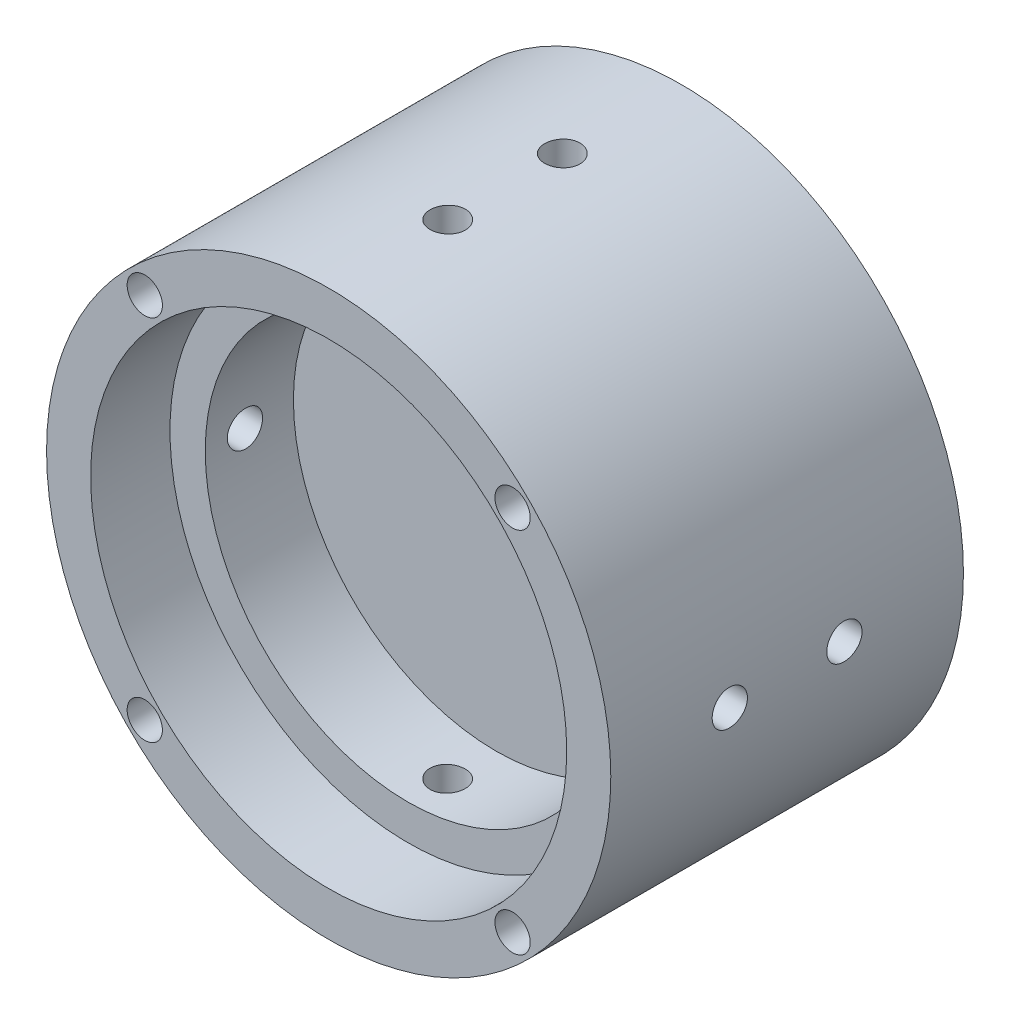
SolidWorks part; units mm, degrees
ref_plane "Front Plane" through (0, 0, 0) normal (0, 0, 1) x (1, 0, 0)
ref_plane "Top Plane" through (0, 0, 0) normal (0, 1, 0) x (1, 0, 0)
ref_plane "Right Plane" through (0, 0, 0) normal (1, 0, 0) x (0, 0, -1)
sketch "Sketch1" plane through (0, 0, 0) normal (0, 0, 1) x (1, 0, 0)
  circle A0 centre (0, 0) radius 80
extrude "Boss-Extrude1" add sketch "Sketch1" along normal blind 100
sketch "Sketch2" plane through (0, 0, 100) normal (0, 0, 1) x (1, 0, 0)
  circle A0 centre (0, 0) radius 67.5
extrude "Cut-Extrude1" cut sketch "Sketch2" against normal blind 22.5 contours A0
sketch "Sketch3" plane through (0, 0, 77.5) normal (0, 0, 1) x (1, 0, 0)
  circle A0 centre (0, 0) radius 57.5
extrude "Cut-Extrude2" cut sketch "Sketch3" against normal blind 25
sketch "Sketch6" plane through (0, 0, 0) normal (0, 1, 0) x (1, 0, 0)
  circle A0 centre (0, -66.25) radius 5
  point P6 (6.6984, -66.25)
  point P7 (0, 0)
extrude "Cut-Extrude3" cut sketch "Sketch6" against normal blind 184 and the other way blind 175
sketch "Sketch7" plane through (0, 0, 0) normal (1, 0, 0) x (0, 0, -1)
  line L0 (-100, 0) -> (-66.25, 0)
  line L1 (-100, 80) -> (-100, -80) construction
  circle A0 centre (-66.25, 0) radius 5
extrude "Cut-Extrude4" cut sketch "Sketch7" against normal blind 199 and the other way blind 233 contours A0
sketch "Sketch8" plane through (0, 0, 0) normal (0, 0, 1) x (1, 0, 0)
  circle A0 centre (0, 0) radius 67.5
extrude "Cut-Extrude5" cut sketch "Sketch8" along normal blind 22.5
sketch "Sketch9" plane through (0, 0, 0) normal (0, 0, 1) x (1, 0, 0)
  circle A0 centre (0, 0) radius 57.5
extrude "Cut-Extrude6" cut sketch "Sketch9" along normal blind 45
sketch "Sketch10" plane through (0, 0, 0) normal (0, 0, 1) x (1, 0, 0)
  line L0 (0, 0) -> (-56.5685, 56.5685)
  line L1 (56.5685, 56.5685) -> (-56.5685, -56.5685)
  line L2 (-56.5685, 56.5685) -> (-47.7297, 47.7297)
  circle A0 centre (0, 0) radius 80 construction
  circle A2 centre (-52.1491, 52.1491) radius 5
  circle A3 centre (52.1491, 52.1491) radius 5
  circle A4 centre (52.1491, -52.1491) radius 5
  circle A5 centre (-52.1491, -52.1491) radius 5
  point P19 (0, 0)
  dimension "D1" = 4
extrude "Cut-Extrude9" cut sketch "Sketch10" along normal blind 114 contours A2 | A3 | A4 | A5
sketch "Sketch11" plane through (0, 0, 0) normal (1, 0, 0) x (0, 0, -1)
  line L0 (0, 0) -> (-33.75, 0)
  circle A0 centre (-33.75, 0) radius 5
extrude "Cut-Extrude10" cut sketch "Sketch11" against normal blind 116 and the other way blind 87 contours A0
sketch "Sketch12" plane through (0, 0, 0) normal (0, 1, 0) x (1, 0, 0)
  line L0 (0, 0) -> (0, -33.75)
  circle A0 centre (0, -33.75) radius 5
extrude "Cut-Extrude11" cut sketch "Sketch12" against normal blind 109 and the other way blind 94 contours A0
